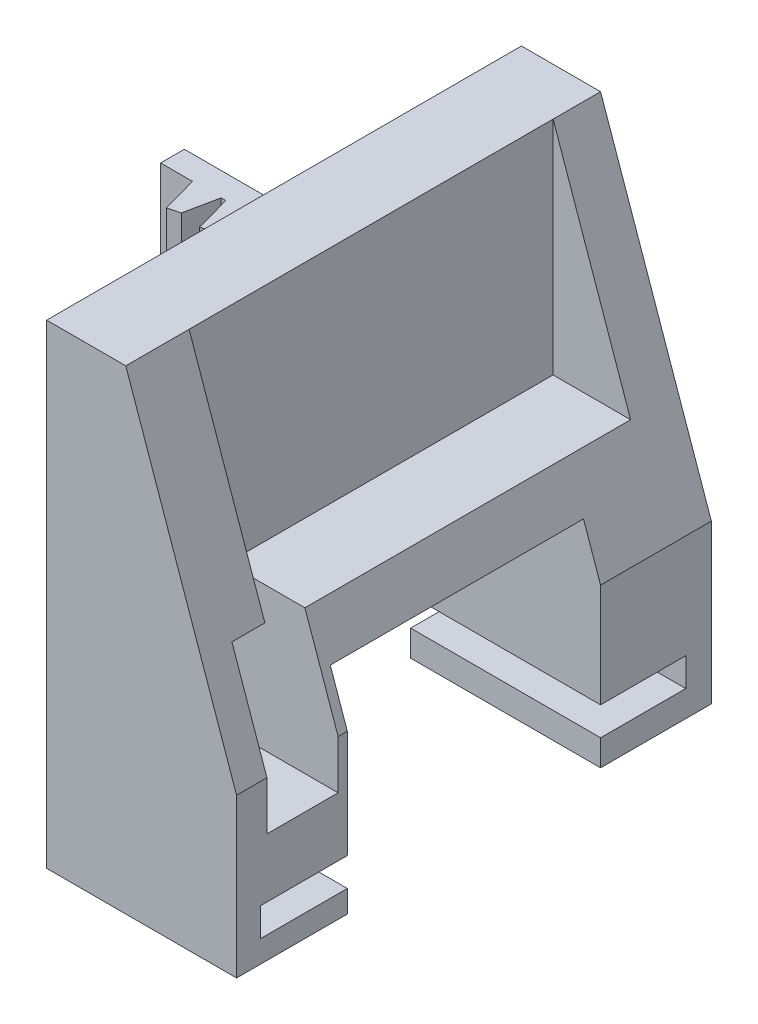
SolidWorks part; units mm, degrees
ref_plane "Front Plane" through (0, 0, 0) normal (0, 0, 1) x (1, 0, 0)
ref_plane "Top Plane" through (0, 0, 0) normal (0, 1, 0) x (1, 0, 0)
ref_plane "Right Plane" through (0, 0, 0) normal (1, 0, 0) x (0, 0, -1)
sketch "Sketch1" plane through (0, 0, 0) normal (0, 0, 1) x (1, 0, 0)
  line L0 (0, 0) -> (0, -30)
  line L1 (0, -30) -> (12, -30)
  line L2 (12, -30) -> (12, -20)
  line L3 (12, -20) -> (5, 0)
  line L4 (5, 0) -> (0, 0)
  dimension "D1" = 30
  dimension "D2" = 12
  dimension "D3" = 10
  dimension "D4" = 5
extrude "Boss-Extrude1" add sketch "Sketch1" against normal blind 30
sketch "Sketch4" plane through (0, 0, 0) normal (-1, 0, 0) x (0, 0, 1)
  line L0 (-30, 0) -> (-30, -30) construction
  line L1 (-23, -16.9179) -> (-7, -16.9179)
  line L2 (-23, -16.9179) -> (-23, -30.9179)
  line L3 (-23, -30.9179) -> (-7, -30.9179)
  line L4 (-7, -16.9179) -> (-7, -30.9179)
  point P4 (-23, -23.9179)
  dimension "D1" = 16
  dimension "D2" = 14
  dimension "D3" = 7
extrude "Cut-Extrude2" cut sketch "Sketch4" against normal blind 25 contours L2 L1 L4 L3
sketch "Sketch5" plane through (0, 0, 0) normal (-1, 0, 0) x (0, 0, 1)
  line L0 (-7, -16.9179) -> (-7, -30) construction
  line L1 (-7, -26.8) -> (-1.5, -26.8)
  line L2 (-7, -26.8) -> (-7, -28.6)
  line L3 (-7, -28.6) -> (-1.5, -28.6)
  line L4 (-1.5, -26.8) -> (-1.5, -28.6)
  line L5 (-7, -30) -> (0, -30) construction
  dimension "D1" = 1.8
  dimension "D2" = 5.5
  dimension "D3" = 1.4
extrude "Cut-Extrude3" cut sketch "Sketch5" against normal blind 15
ref_plane "Plane1" through (0, 0, -15.5) normal (0, 0, 1) x (1, 0, 0)
sketch "Sketch6" plane through (0, 0, -15.5) normal (0, 0, 1) x (1, 0, 0)
  line L0 (5, 0) -> (5, -14)
  line L1 (5, -14) -> (9.9, -14)
  line L2 (12, -20) -> (5, 0) construction
  line L3 (9.9, -14) -> (5, 0)
  dimension "D1" = 14
extrude "Cut-Extrude4" cut sketch "Sketch6" against normal mid plane 23
ref_plane "Plane2" through (0, -22, 0) normal (0, 1, 0) x (1, 0, 0)
sketch "Sketch7" plane through (0, -22, 0) normal (0, 1, 0) x (1, 0, 0)
  line L0 (0, 27.7) -> (-19, 27.7)
  line L1 (0, 30) -> (0, 0) construction
  line L3 (0, 27.7) -> (0, 26.2)
  line L4 (0, 26.2) -> (-0.5, 26.2)
  line L47 (-0.5, 26.2) -> (-0.9304, 24.1151)
  line L62 (-16.5, 15.5) -> (16.5, 15.5) construction
  line L108 (-19, 26.2) -> (-19, 27.7)
  line L112 (-0.9304, 24.1151) -> (-1.6865, 23.9276)
  line L113 (-2.3144, 26.2) -> (-2.597, 26.2)
  line L114 (-3.0274, 24.1151) -> (-3.7835, 23.9276)
  line L115 (-2.597, 26.2) -> (-3.0274, 24.1151)
  line L116 (-5.1244, 24.1151) -> (-5.8805, 23.9276)
  line L117 (-4.694, 26.2) -> (-5.1244, 24.1151)
  line L118 (-7.2214, 24.1151) -> (-7.9775, 23.9276)
  line L119 (-6.791, 26.2) -> (-7.2214, 24.1151)
  line L120 (-9.3184, 24.1151) -> (-10.0745, 23.9276)
  line L121 (-8.888, 26.2) -> (-9.3184, 24.1151)
  line L122 (-11.4154, 24.1151) -> (-12.1715, 23.9276)
  line L123 (-10.985, 26.2) -> (-11.4154, 24.1151)
  line L124 (-13.5124, 24.1151) -> (-14.2685, 23.9276)
  line L125 (-13.082, 26.2) -> (-13.5124, 24.1151)
  line L126 (-4.4114, 26.2) -> (-4.694, 26.2)
  line L127 (-6.5085, 26.2) -> (-6.791, 26.2)
  line L128 (-8.6055, 26.2) -> (-8.888, 26.2)
  line L129 (-10.7025, 26.2) -> (-10.985, 26.2)
  line L130 (-12.7995, 26.2) -> (-13.082, 26.2)
  line L132 (-15.6094, 24.1151) -> (-16.3655, 23.9276)
  line L133 (-15.179, 26.2) -> (-15.6094, 24.1151)
  line L134 (-14.8965, 26.2) -> (-15.179, 26.2)
  line L135 (-16.9935, 26.2) -> (-19, 26.2)
  arc A0 (-1.6865, 23.9276) -> (-2.3144, 26.2) centre (-44.8671, 13.2176) ccw
  arc A1 (-3.7835, 23.9276) -> (-4.4114, 26.2) centre (-46.9641, 13.2176) ccw
  arc A2 (-5.8805, 23.9276) -> (-6.5085, 26.2) centre (-49.0611, 13.2176) ccw
  arc A3 (-7.9775, 23.9276) -> (-8.6055, 26.2) centre (-51.1581, 13.2176) ccw
  arc A4 (-10.0745, 23.9276) -> (-10.7025, 26.2) centre (-53.2551, 13.2176) ccw
  arc A5 (-12.1715, 23.9276) -> (-12.7995, 26.2) centre (-55.3521, 13.2176) ccw
  arc A6 (-14.2685, 23.9276) -> (-14.8965, 26.2) centre (-57.4491, 13.2176) ccw
  arc A7 (-16.3655, 23.9276) -> (-16.9935, 26.2) centre (-59.5461, 13.2176) ccw
  dimension "D1" = 7
  dimension "D4" = 8
  dimension "D2" = 19
  dimension "D3" = 1.5
  dimension "D6" = 0.5
  dimension "D7" = 12.2
extrude "Boss-Extrude2" add sketch "Sketch7" along normal blind 8
sketch "Sketch8" plane through (0, 0, 0) normal (-1, 0, 0) x (0, 0, 1)
  line L0 (-6.4185, -13.6747) -> (-1.9185, -13.6747)
  line L6 (-1.9185, -13.6747) -> (-1.9185, -23.0747)
  line L7 (-1.9185, -23.0747) -> (-6.4185, -23.0747)
  line L9 (-6.4185, -23.0747) -> (-6.4185, -13.6747)
  dimension "D1" = 4.5
  dimension "D2" = 9.4
extrude "Cut-Extrude5" cut sketch "Sketch8" against normal through all
sketch "Sketch9" plane through (0, 0, 0) normal (-1, 0, 0) x (0, 0, 1)
  line L1 (-28.3853, -26.5537) -> (-22.8853, -26.5537)
  line L2 (-28.3853, -26.5537) -> (-28.3853, -28.3537)
  line L3 (-28.3853, -28.3537) -> (-22.8853, -28.3537)
  line L4 (-22.8853, -26.5537) -> (-22.8853, -28.3537)
  dimension "D1" = 1.8
  dimension "D2" = 5.5
extrude "Cut-Extrude6" cut sketch "Sketch9" against normal through all
